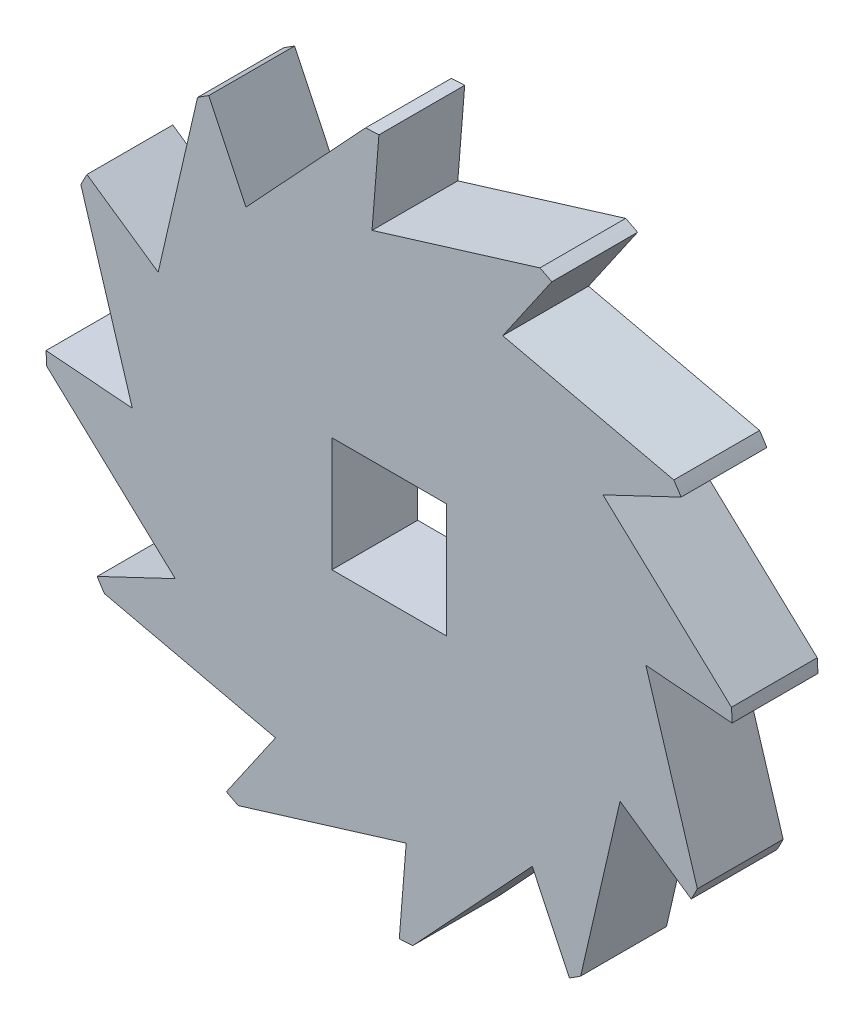
SolidWorks part; units mm, degrees
ref_plane "Front Plane" through (0, 0, 0) normal (0, 0, 1) x (1, 0, 0)
ref_plane "Top Plane" through (0, 0, 0) normal (0, 1, 0) x (1, 0, 0)
ref_plane "Right Plane" through (0, 0, 0) normal (1, 0, 0) x (0, 0, -1)
sketch "Sketch1" plane through (0, 0, 0) normal (0, 0, 1) x (1, 0, 0)
  line L0 (-0.89, 29.9868) -> (-1.4937, 22.45)
  line L1 (-5, -5) -> (5, -5)
  line L2 (-5, -5) -> (-5, 5)
  line L3 (-5, 5) -> (5, 5)
  line L4 (5, -5) -> (5, 5)
  line L5 (-5, -5) -> (5, 5) construction
  line L6 (-5, 5) -> (5, -5) construction
  line L7 (-1.4937, 22.45) -> (13.1829, 26.9483)
  line L8 (14.2226, 26.4143) -> (9.9314, 20.1891)
  line L9 (9.9314, 20.1891) -> (24.8909, 16.7465)
  line L10 (25.5243, 15.7642) -> (18.6954, 12.5186)
  line L11 (18.6954, 12.5186) -> (29.9294, 2.0574)
  line L12 (29.9868, 0.89) -> (22.45, 1.4937)
  line L13 (22.45, 1.4937) -> (26.9483, -13.1829)
  line L14 (26.4143, -14.2226) -> (20.1891, -9.9314)
  line L15 (20.1891, -9.9314) -> (16.7465, -24.8909)
  line L16 (15.7642, -25.5243) -> (12.5186, -18.6954)
  line L17 (12.5186, -18.6954) -> (2.0574, -29.9294)
  line L18 (0.89, -29.9868) -> (1.4937, -22.45)
  line L19 (1.4937, -22.45) -> (-13.1829, -26.9483)
  line L20 (-14.2226, -26.4143) -> (-9.9314, -20.1891)
  line L21 (-9.9314, -20.1891) -> (-24.8909, -16.7465)
  line L22 (-25.5243, -15.7642) -> (-18.6954, -12.5186)
  line L23 (-18.6954, -12.5186) -> (-29.9294, -2.0574)
  line L24 (-29.9868, -0.89) -> (-22.45, -1.4937)
  line L25 (-22.45, -1.4937) -> (-26.9483, 13.1829)
  line L26 (-26.4143, 14.2226) -> (-20.1891, 9.9314)
  line L27 (-20.1891, 9.9314) -> (-16.7465, 24.8909)
  line L28 (-15.7642, 25.5243) -> (-12.5186, 18.6954)
  line L29 (-12.5186, 18.6954) -> (-2.0574, 29.9294)
  circle A0 centre (0, 0) radius 30
  point P0 (0, 0)
  point P47 (0, 0)
  dimension "D2" = 60
  dimension "D1" = 10
  dimension "D3" = 17.45
  dimension "D4" = 4.58
  dimension "D5" = 68.38
  dimension "D6" = 4.11
  dimension "D7" = 12
extrude "Boss-Extrude1" add sketch "Sketch1" along normal blind 7.5 contours L12 A0 L11 L10 L9 L8 L7 L0 L29 L28 L27 L26 L25 L24 L23 L22 L21 L20 L19 L18 L17 L16 L15 L14 L13 L4 L1 L2 L3
